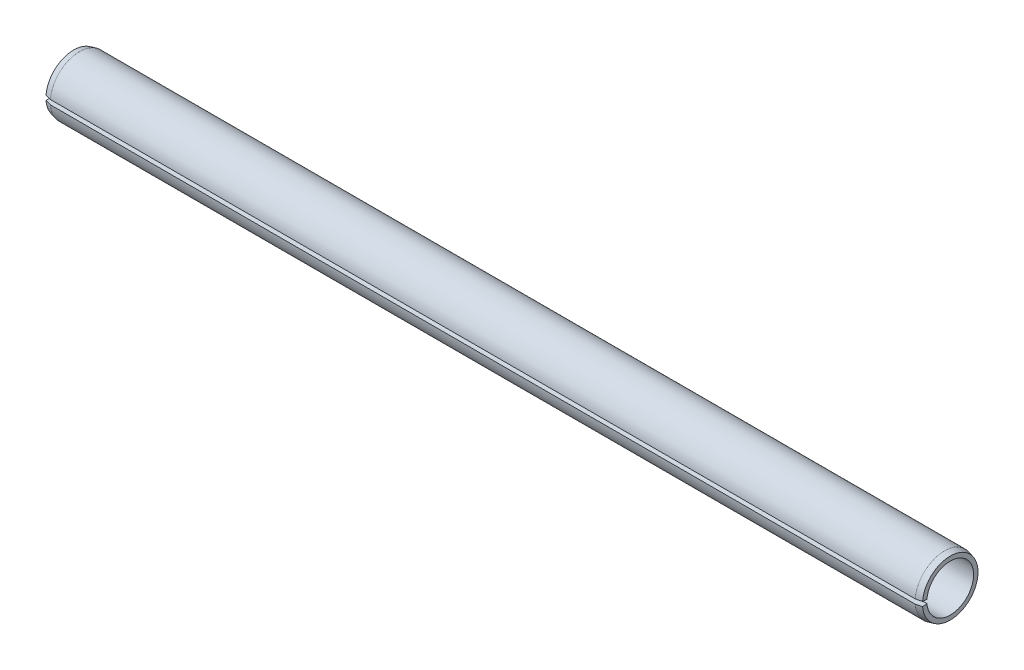
SolidWorks part; units mm, degrees
ref_plane "Plane1" through (0, 0, 0) normal (0, 0, 1) x (1, 0, 0)
ref_plane "Plane2" through (0, 0, 0) normal (0, 1, 0) x (1, 0, 0)
ref_plane "Plane3" through (0, 0, 0) normal (1, 0, 0) x (0, 0, -1)
sketch "Sketch1" plane through (0, 0, 0) normal (0, 0, 1) x (1, 0, 0)
  line L0 (-9.525, 0) -> (111.125, 0) construction
  line L1 (0, 0.8) -> (30, 0.8)
  line L2 (30, 0.8) -> (30, 0.95)
  line L3 (30, 0.95) -> (29.8, 1)
  line L4 (29.8, 1) -> (0.2, 1)
  line L5 (0.2, 1) -> (0, 0.95)
  line L7 (0, 0.95) -> (0, 0.8)
revolve "Base-Revolve" add sketch "Sketch1" angle 360 about L0
sketch "Sketch2" plane through (0, 0, 0) normal (-1, 0, 0) x (0, -1, 0)
  line L0 (0, 0) -> (0.08, 1.0169)
  line L1 (0, -3.175) -> (0, 12.7) construction
  line L2 (0, 0) -> (-0.08, 1.0169)
  arc A0 (0.08, 1.0169) -> (-0.08, 1.0169) centre (0, 0) ccw
  dimension "Gap_ang" = 9
extrude "Gap" cut sketch "Sketch2" against normal through all
equation "\"D1@Sketch2\" = \"Diameter@Sketch1\" * 0.51"
equation "\"D1@Sketch1\" = \"Diameter@Sketch1\" -  ( \"Thickness@Sketch1\" / 2 ) "
equation "\"D2@Sketch1\" = \"D1@Sketch1\""
equation "\"D3@Sketch1\" = \"Chamfer_len@Sketch1\""
